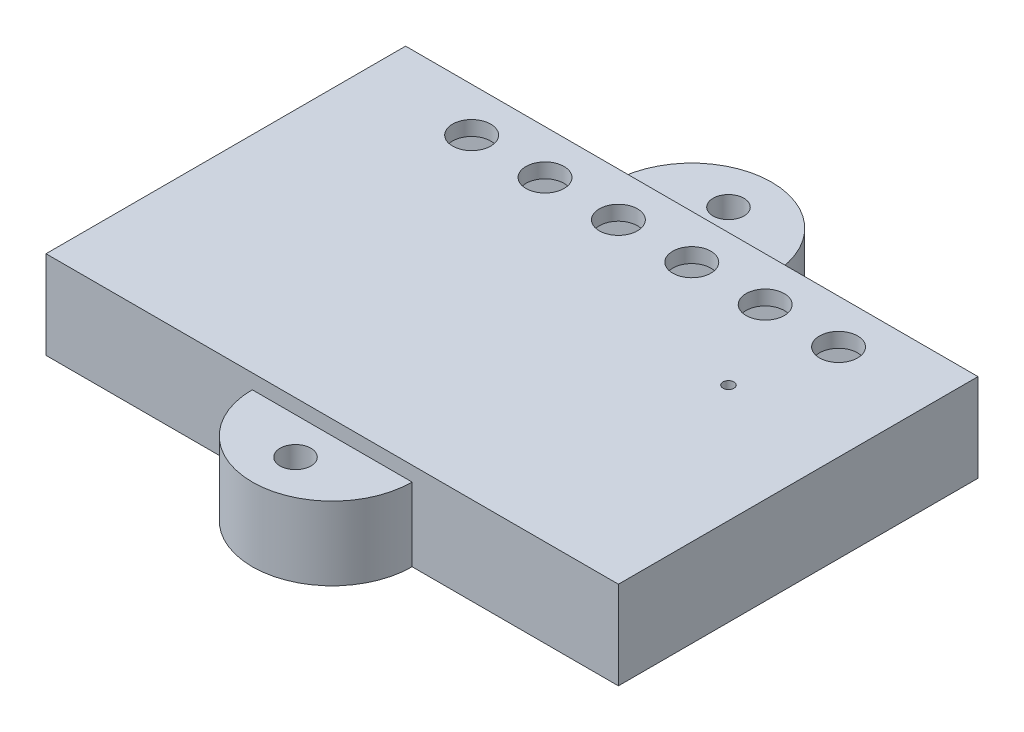
SolidWorks part; units mm, degrees
ref_plane "Front Plane" through (0, 0, 0) normal (0, 0, 1) x (1, 0, 0)
ref_plane "Top Plane" through (0, 0, 0) normal (0, 1, 0) x (1, 0, 0)
ref_plane "Right Plane" through (0, 0, 0) normal (1, 0, 0) x (0, 0, -1)
sketch "Sketch2" plane through (0, 0, 0) normal (0, 1, 0) x (1, 0, 0)
  line L0 (-39, 24.5) -> (-39, 10.89)
  line L1 (-36, 21.5) -> (36, 21.5)
  line L2 (-36, 21.5) -> (-36, -21.5)
  line L3 (-36, -21.5) -> (36, -21.5)
  line L4 (36, 21.5) -> (36, -21.5)
  line L5 (-36, 21.5) -> (36, -21.5) construction
  line L6 (-36, -21.5) -> (36, 21.5) construction
  line L7 (-39, -24.5) -> (-10.89, -24.5)
  line L8 (39, 24.5) -> (39, 10.89)
  line L9 (-39, 24.5) -> (-10.89, 24.5)
  line L10 (39, -10.89) -> (39, -24.5)
  line L11 (39, 24.5) -> (39, -24.5) construction
  line L12 (0, 21.5) -> (0, -21.5) construction
  line L13 (-39, -10.89) -> (-39, -24.5)
  line L14 (-39, 24.5) -> (-39, -24.5) construction
  line L15 (39, -10.89) -> (39, 10.89)
  line L16 (-39, -10.89) -> (-39, 10.89)
  line L17 (10.89, -24.5) -> (39, -24.5)
  line L18 (-39, -24.5) -> (39, -24.5) construction
  line L19 (10.89, 24.5) -> (39, 24.5)
  line L20 (-39, 24.5) -> (39, 24.5) construction
  arc A4 (10.89, 24.5) -> (-10.89, 24.5) centre (0, 24.5) ccw
  circle A5 centre (0, 29.5) radius 2.1
  arc A6 (10.89, -24.5) -> (-10.89, -24.5) centre (0, -24.5) cw
  circle A7 centre (0, -29.5) radius 2.1
  point P0 (0, 0)
  dimension "D4" = 10.89
  dimension "D5" = 4.2
  dimension "D7" = 10.89
  dimension "D8" = 4.2
  dimension "D1" = 78
  dimension "D2" = 43
  dimension "D6" = 5
  dimension "D9" = 5
  dimension "D3" = 3
extrude "Boss-Extrude1" add sketch "Sketch2" along normal blind 10
sketch "Sketch3" plane through (0, 10, 0) normal (0, 1, 0) x (1, 0, 0)
  line L1 (-39, 24.5) -> (39, 24.5)
  line L2 (-39, 24.5) -> (-39, -24.5)
  line L3 (-39, -24.5) -> (39, -24.5)
  line L4 (39, 24.5) -> (39, -24.5)
  circle A0 centre (-24, 18.5) radius 2.6
  circle A1 centre (-14, 18.5) radius 2.6
  circle A2 centre (-4, 18.5) radius 2.6
  circle A3 centre (6, 18.5) radius 2.6
  circle A4 centre (16, 18.5) radius 2.6
  circle A5 centre (26, 18.5) radius 2.6
  dimension "D4" = 5.2
  dimension "D1" = 15
  dimension "D2" = 6
  dimension "D3" = 6
extrude "Boss-Extrude2" add sketch "Sketch3" along normal blind 2
sketch "Sketch4" plane through (0, 12, 0) normal (0, 1, 0) x (1, 0, 0)
  line L0 (39, -24.5) -> (39, 24.5) construction
  line L1 (39, 24.5) -> (-39, 24.5) construction
  circle A0 centre (23, 6.5) radius 0.75
  dimension "D1" = 1.5
  dimension "D2" = 16
  dimension "D3" = 18
extrude "Cut-Extrude1" cut sketch "Sketch4" against normal blind 10
